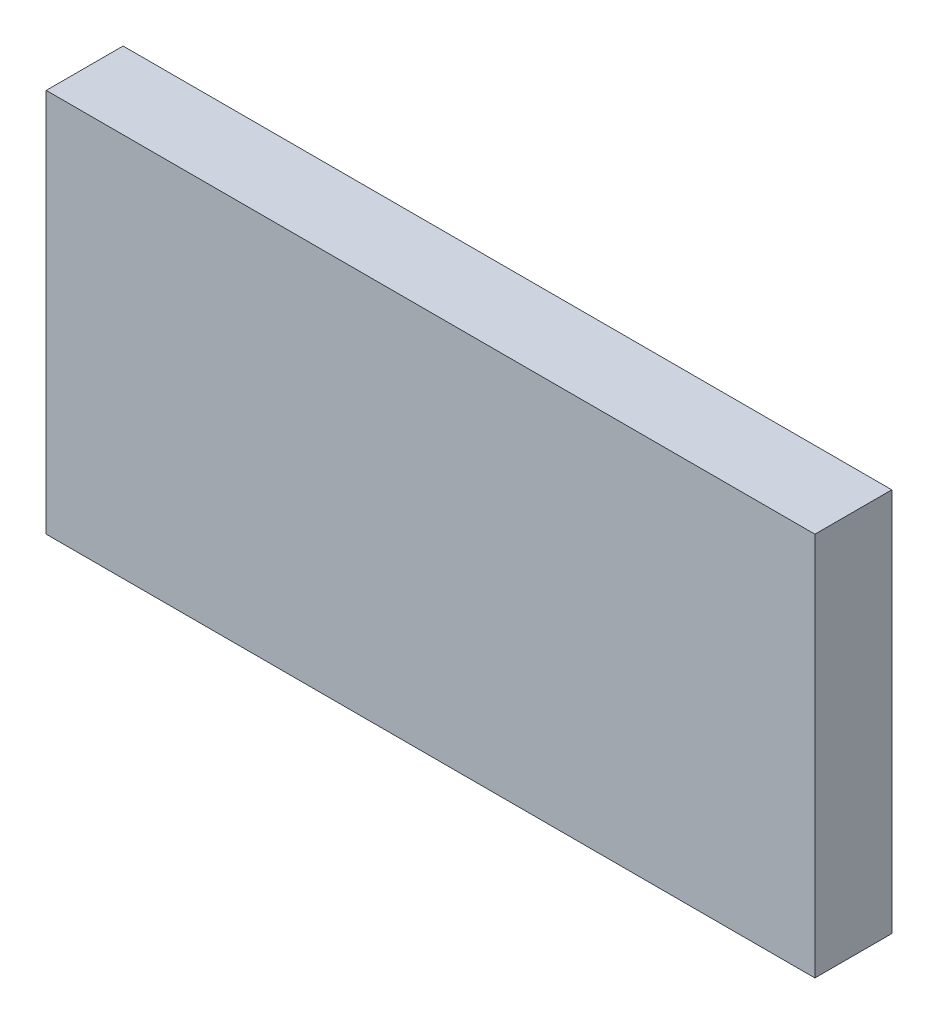
SolidWorks part; units mm, degrees
ref_plane "Front Plane" through (0, 0, 0) normal (0, 0, 1) x (1, 0, 0)
ref_plane "Top Plane" through (0, 0, 0) normal (0, 1, 0) x (1, 0, 0)
ref_plane "Right Plane" through (0, 0, 0) normal (1, 0, 0) x (0, 0, -1)
sketch "Sketch1" plane through (0, 0, 0) normal (0, 0, 1) x (1, 0, 0)
  line L1 (0, 0) -> (40, 0)
  line L2 (0, 0) -> (0, 20)
  line L3 (0, 20) -> (40, 20)
  line L4 (40, 0) -> (40, 20)
extrude "Boss-Extrude1" add sketch "Sketch1" against normal blind 4
